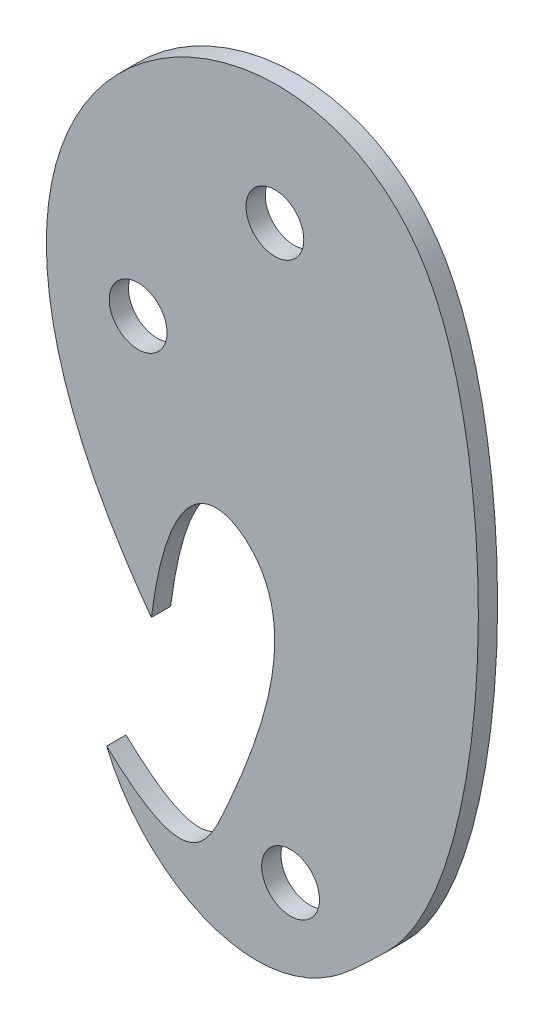
SolidWorks part; units mm, degrees
material "1023 Carbon Steel Sheet (SS)"
ref_plane "Front Plane" through (0, 0, 0) normal (0, 0, 1) x (1, 0, 0)
ref_plane "Top Plane" through (0, 0, 0) normal (0, 1, 0) x (1, 0, 0)
ref_plane "Right Plane" through (0, 0, 0) normal (1, 0, 0) x (0, 0, -1)
sketch "Sketch1" plane through (0, 0, 0) normal (0, 0, 1) x (1, 0, 0)
  line L0 (0, 0) -> (0, 42.5013) construction
  line L5 (-1000, 0) -> (49000, 0) construction
  line L7 (-2.8234, -13.1772) -> (82.4452, -13.1772) construction
  line L8 (-1000.6846, -21.4891) -> (48999.3154, -21.4891) construction
  line L11 (25.8334, -1009.5207) -> (25.8334, 48990.4793) construction
  circle A0 centre (0, 0) radius 21.5 construction
  circle A1 centre (10, 29.8706) radius 10 construction
  arc A2 (10, 29.8706) -> (25.8334, -13.1772) centre (-30.6017, -9.4988) cw construction
  circle A3 centre (24.2037, 45.3384) radius 3
  circle A4 centre (24.2037, 45.3384) radius 11 construction
  circle A5 centre (10, 29.8706) radius 3
  circle A6 centre (25.8334, -13.1772) radius 3
  circle A7 centre (25.8334, -13.1772) radius 7.5 construction
  arc A8 (32.1941, -17.8102) -> (35.7876, -14.4141) centre (-69.0252, 92.8905) ccw
  arc A12 (24.2037, 45.3384) -> (25.8334, -13.1772) centre (-26.7418, 14.6391) cw construction
  spline S0 degree 3 poles (11.379, 3.4633) (-20.4281, 46.5614) (31.036, 75.2628) (47.8347, 28.3572) (45.4685, -4.9579) (35.7876, -14.4141) knots 0 0 0 0 0.5991 0.662518 0.977568 0.977568 0.977568 0.977568
  spline S1 degree 3 poles (11.379, 3.4633) (13.3658, 19.1009) (28.9264, 15.3503) (21.064, -6.3958) (15.1535, -18.3535) (6.7411, -10.4207) knots 0 0 0 0 0.266778 0.750923 1 1 1 1
  spline S2 degree 3 poles (6.7411, -10.4207) (10.446, -19.7089) (22.4444, -26.7248) (32.1941, -17.8102) knots 0 0 0 0 0.946117 0.946117 0.946117 0.946117
  point P9 (22.4766, 10.0239)
  point P21 (32.7153, 16.295)
  dimension "D1" = 43
  dimension "D2" = 20
  dimension "D4" = 22
  dimension "D8" = 15
  dimension "D6" = 150
  dimension "D3" = 6
  dimension "D5" = 47.846
  dimension "D10" = 58.955
extrude "Boss-Extrude1" add sketch "Sketch1" along normal blind 2
